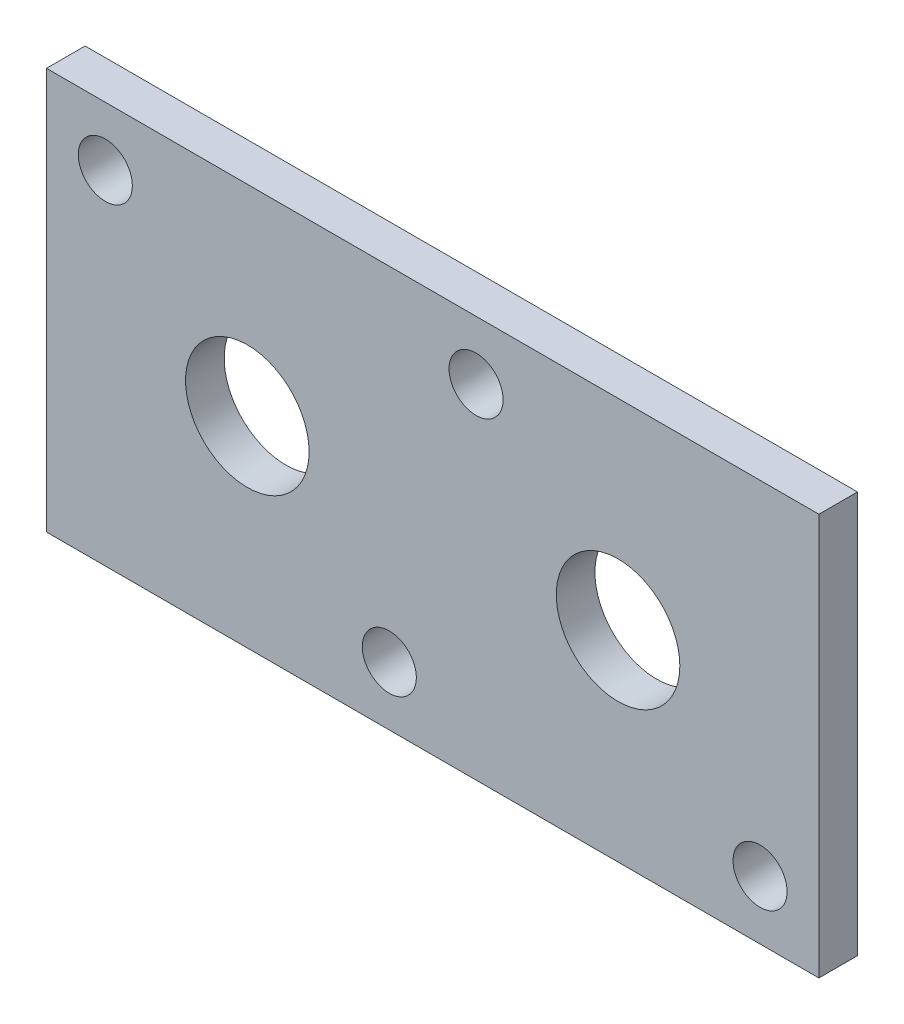
SolidWorks part; units mm, degrees
ref_plane "정면" through (0, 0, 0) normal (0, 0, 1) x (1, 0, 0)
ref_plane "윗면" through (0, 0, 0) normal (0, 1, 0) x (1, 0, 0)
ref_plane "우측면" through (0, 0, 0) normal (1, 0, 0) x (0, 0, -1)
sketch "스케치1" plane through (0, 0, 0) normal (0, 0, 1) x (1, 0, 0)
  line L0 (-24, 29.1233) -> (-24, -29.3484) construction
  line L1 (-50, 26) -> (50, 26)
  line L2 (-50, 26) -> (-50, -26)
  line L3 (-50, -26) -> (50, -26)
  line L4 (50, 26) -> (50, -26)
  line L5 (-50, 26) -> (50, -26) construction
  line L6 (-50, -26) -> (50, 26) construction
  line L7 (-53.6978, 29.6978) -> (6.8397, -30.8397) construction
  line L8 (0, 30.5742) -> (0, -34.7431) construction
  line L9 (24, 30.5742) -> (24, -30.8397) construction
  line L10 (0.2032, 23.7968) -> (53.7596, -29.7596) construction
  circle A0 centre (24, 0) radius 8
  circle A1 centre (-24, 0) radius 8
  circle A2 centre (-42.3848, 18.3848) radius 3.5
  circle A3 centre (-5.6152, -18.3848) radius 3.5
  circle A4 centre (5.6152, 18.3848) radius 3.5
  circle A5 centre (42.3848, -18.3848) radius 3.5
  point P0 (0, 0)
  dimension "D3" = 16
  dimension "D9" = 7
  dimension "D10" = 26
  dimension "D13" = 7
  dimension "D14" = 26
  dimension "D1" = 52
  dimension "D2" = 100
  dimension "D4" = 26
  dimension "D5" = 26
  dimension "D6" = 26
  dimension "D7" = 26
  dimension "D8" = 45
  dimension "D11" = 26
  dimension "D12" = 45
  dimension "D15" = 26
extrude "보스-돌출1" add sketch "스케치1" along normal blind 5
